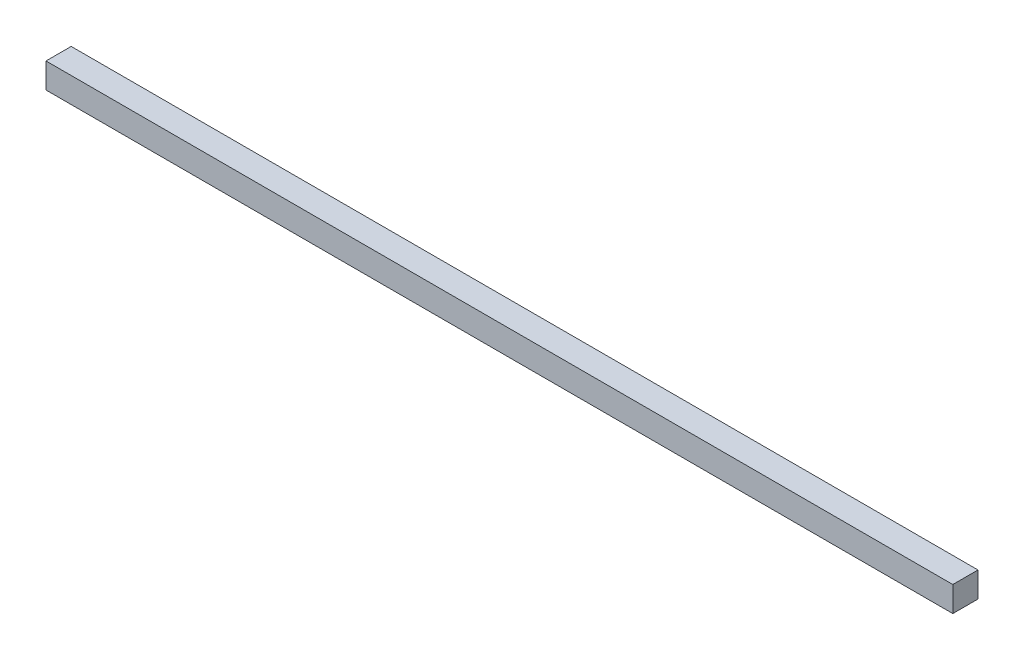
SolidWorks part; units mm, degrees
ref_plane "正面" through (0, 0, 0) normal (0, 0, 1) x (1, 0, 0)
ref_plane "平面" through (0, 0, 0) normal (0, 1, 0) x (1, 0, 0)
ref_plane "右側面" through (0, 0, 0) normal (1, 0, 0) x (0, 0, -1)
sketch "ｽｹｯﾁ1" plane through (0, 0, 0) normal (0, 0, 1) x (1, 0, 0)
  line L1 (-82.1516, 9.9786) -> (97.8484, 9.9786)
  line L2 (-82.1516, 9.9786) -> (-82.1516, 4.9786)
  line L3 (-82.1516, 4.9786) -> (97.8484, 4.9786)
  line L4 (97.8484, 9.9786) -> (97.8484, 4.9786)
  dimension "D3" = 5
  dimension "D4" = 180
extrude "ﾎﾞｽ - 押し出し1" add sketch "ｽｹｯﾁ1" along normal blind 5
